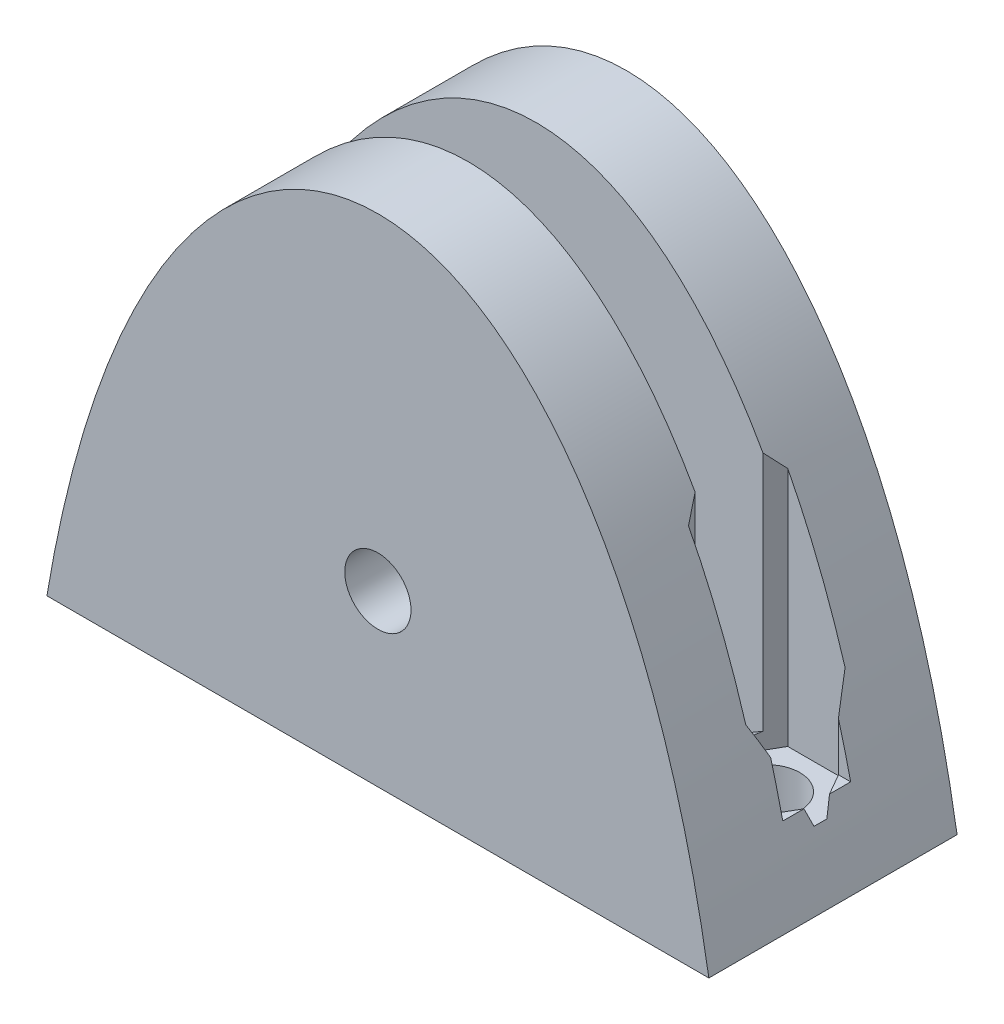
SolidWorks part; units mm, degrees
ref_plane "Front Plane" through (0, 0, 0) normal (0, 0, 1) x (1, 0, 0)
ref_plane "Top Plane" through (0, 0, 0) normal (0, 1, 0) x (1, 0, 0)
ref_plane "Right Plane" through (0, 0, 0) normal (1, 0, 0) x (0, 0, -1)
sketch "Sketch1" plane through (0, 0, 0) normal (0, 0, 1) x (1, 0, 0)
  line L0 (-20, 0) -> (20, 0)
  line L1 (-20, 0) -> (-20, 30) construction
  line L2 (-20, 30) -> (0, 40) construction
  line L3 (0, 40) -> (20, 30) construction
  line L4 (20, 30) -> (20, 0) construction
  line L5 (20, 0) -> (15, 30) construction
  line L6 (15, 30) -> (-15, 30) construction
  line L7 (-15, 30) -> (-20, 0) construction
  line L8 (-20, 0) -> (-15, 30) construction
  line L9 (-15, 30) -> (0, 40) construction
  line L10 (0, 40) -> (15, 30) construction
  line L11 (15, 30) -> (20, 0) construction
  spline S0 degree 4 poles (-20, 0) (-15, 30) (0, 40) (15, 30) (20, 0) knots 0 0 0 0 0 1 1 1 1 1
  point P5 (0, 0)
  point P8 (20, 40)
  point P13 (0, 0)
  point P14 (0, 50)
  point P15 (15, 40)
  point P16 (-15, 40)
  dimension "D1" = 40
  dimension "D2" = 40
  dimension "D3" = 30
  dimension "D4" = 5
  dimension "D5" = 5
extrude "Boss-Extrude1" add sketch "Sketch1" along normal blind 15
sketch "Sketch2" plane through (0, 0, 0) normal (0, -1, 0) x (1, 0, 0)
  line L0 (-20, 15) -> (20, 15) construction
  line L1 (20, 0) -> (12, 0)
  line L2 (20, 0) -> (20, 15)
  line L3 (20, 15) -> (12, 15)
  line L4 (12, 0) -> (12, 15)
  line L5 (20, 0) -> (12, 15) construction
  line L6 (-20, 0) -> (-12, 0)
  line L7 (-20, 0) -> (-20, 15)
  line L8 (-20, 15) -> (-12, 15)
  line L9 (-12, 0) -> (-12, 15)
  line L10 (-20, 0) -> (-12, 15) construction
  circle A0 centre (16, 7.5) radius 2
  circle A1 centre (-16, 7.5) radius 2
  dimension "D3" = 4
  dimension "D4" = 4
  dimension "D1" = 8
  dimension "D2" = 8
extrude "Cut-Extrude1" cut sketch "Sketch2" against normal up to surface (8.9591 mm away) contours A0 | A1
ref_plane "Plane1" through (0, 4, 0) normal (0, -1, 0) x (-1, 0, 0)
sketch "Sketch3" plane through (0, 4, 0) normal (0, -1, 0) x (-1, 0, 0)
  line L1 (17.7321, -4.5) -> (14.2679, -4.5)
  line L2 (14.2679, -4.5) -> (12.5359, -7.5)
  line L3 (12.5359, -7.5) -> (14.2679, -10.5)
  line L4 (14.2679, -10.5) -> (17.7321, -10.5)
  line L5 (17.7321, -10.5) -> (19.4641, -7.5)
  line L6 (19.4641, -7.5) -> (17.7321, -4.5)
  line L7 (-17.7321, -4.5) -> (-19.4641, -7.5)
  line L8 (-19.4641, -7.5) -> (-17.7321, -10.5)
  line L9 (-17.7321, -10.5) -> (-14.2679, -10.5)
  line L10 (-14.2679, -10.5) -> (-12.5359, -7.5)
  line L11 (-12.5359, -7.5) -> (-14.2679, -4.5)
  line L12 (-14.2679, -4.5) -> (-17.7321, -4.5)
  circle A0 centre (16, -7.5) radius 3 construction
  circle A1 centre (-16, -7.5) radius 3 construction
  point P10 (17.6923, -4.4774)
  point P19 (19.4641, -7.5)
  point P20 (-19.4641, -7.5)
  dimension "D1" = 6
  dimension "D2" = 6
extrude "Cut-Extrude2" cut sketch "Sketch3" against normal up to surface (5.8646 mm away)
sketch "Sketch4" plane through (0, 0, 15) normal (0, 0, 1) x (1, 0, 0)
  line L0 (0, 0) -> (0, 10.25) construction
  line L1 (-20, 0) -> (20, 0) construction
  circle A0 centre (0, 10.25) radius 2
  dimension "D2" = 4
  dimension "D1" = 10.25
extrude "Cut-Extrude3" cut sketch "Sketch4" against normal up to surface (15 mm away) up to face at (10, 0, 0)
ref_plane "Plane2" through (0, 31, 0) normal (0, 1, 0) x (1, 0, 0)
sketch "Sketch5" plane through (0, 31, 0) normal (0, 1, 0) x (1, 0, 0)
  line L0 (20, -15) -> (-20, 0) construction
  line L6 (-20, -15) -> (-20, 0) construction
  line L7 (20, -9.55) -> (-20, -9.55)
  line L11 (20, -9.55) -> (20, -5.45)
  line L12 (20, -5.45) -> (-20, -5.45)
  line L13 (-20, -9.55) -> (-20, -5.45)
  line L14 (20, -9.55) -> (-20, -5.45) construction
  line L15 (20, -5.45) -> (-20, -9.55) construction
  point P4 (0, -7.5)
  dimension "D1" = 4.1
extrude "Cut-Extrude4" cut sketch "Sketch5" against normal offset from surface (26 mm away) 5 up to face at (18, 0, 7.5)
sketch "Sketch7" plane through (0, 0, 9.55) normal (0, 0, -1) x (-1, 0, 0)
  line L0 (13.7195, 5) -> (13.7195, 6.2447)
  line L1 (13.7195, 6.2447) -> (-13.7195, 6.2447)
  line L2 (-13.7195, 19.5635) -> (-13.7195, 5) construction
  line L3 (-13.7195, 6.2447) -> (-13.7195, 5)
  arc A0 (-13.7195, 5) -> (13.7195, 5) centre (0, 26.714) ccw
extrude "Cut-Extrude6" cut sketch "Sketch7" along normal up to surface (4.1 mm away) up to face at (-2, 10.25, 5.45)
